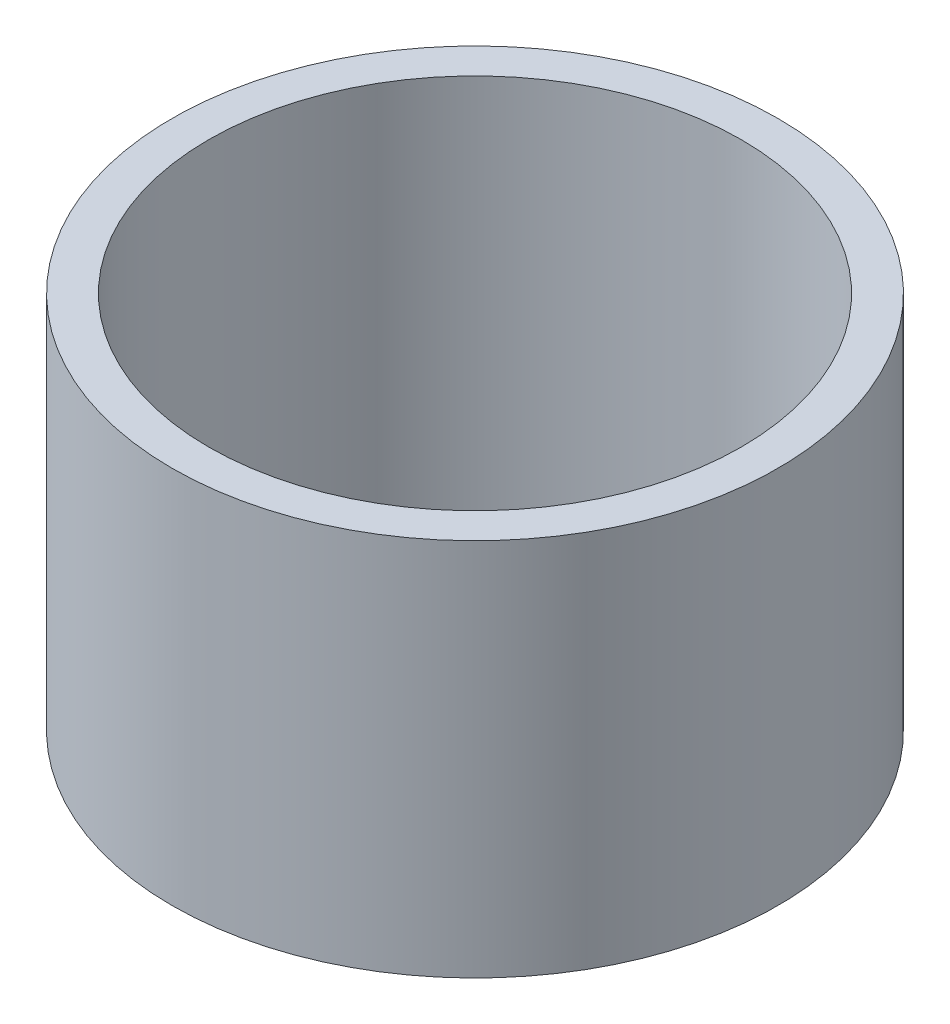
SolidWorks part; units mm, degrees
ref_plane "Front Plane" through (0, 0, 0) normal (0, 0, 1) x (1, 0, 0)
ref_plane "Top Plane" through (0, 0, 0) normal (0, 1, 0) x (1, 0, 0)
ref_plane "Right Plane" through (0, 0, 0) normal (1, 0, 0) x (0, 0, -1)
sketch "Sketch1" plane through (0, 0, 0) normal (0, 1, 0) x (1, 0, 0)
  circle A0 centre (0, 0) radius 12.8
  dimension "D1" = 25.6
extrude "Boss-Extrude1" add sketch "Sketch1" along normal blind 16
sketch "Sketch3" plane through (0, 16, 0) normal (0, 1, 0) x (1, 0, 0)
  circle A0 centre (0, 0) radius 11.25
  dimension "D1" = 22.5
extrude "Cut-Extrude2" cut sketch "Sketch3" against normal through all
